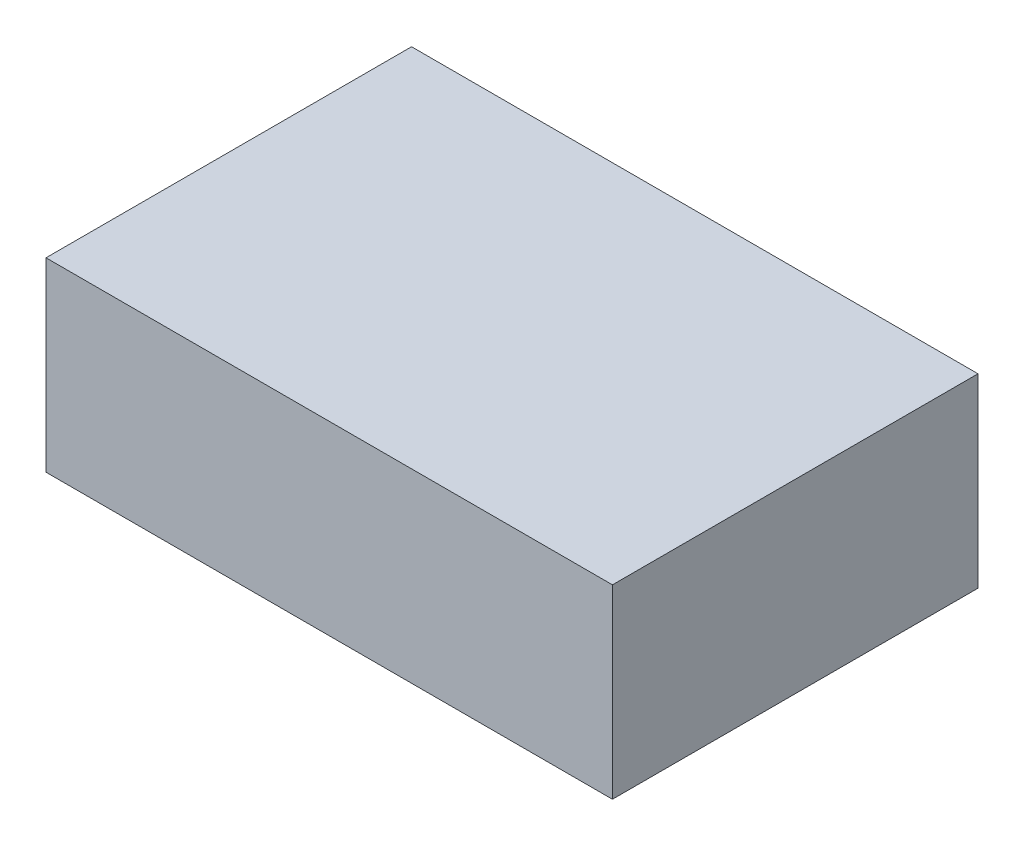
SolidWorks part; units mm, degrees
ref_plane "Front Plane" through (0, 0, 0) normal (0, 0, 1) x (1, 0, 0)
ref_plane "Top Plane" through (0, 0, 0) normal (0, 1, 0) x (1, 0, 0)
ref_plane "Right Plane" through (0, 0, 0) normal (1, 0, 0) x (0, 0, -1)
sketch "草圖1" plane through (0, 0, 0) normal (0, 0, 1) x (1, 0, 0)
  line L0 (-9.15, -3) -> (9.15, -3)
  line L1 (9.15, -3) -> (9.15, 3)
  line L2 (9.15, 3) -> (-9.15, 3)
  line L3 (-9.15, 3) -> (-9.15, -3)
extrude "填料-伸長1" add sketch "草圖1" along normal blind 11.81
